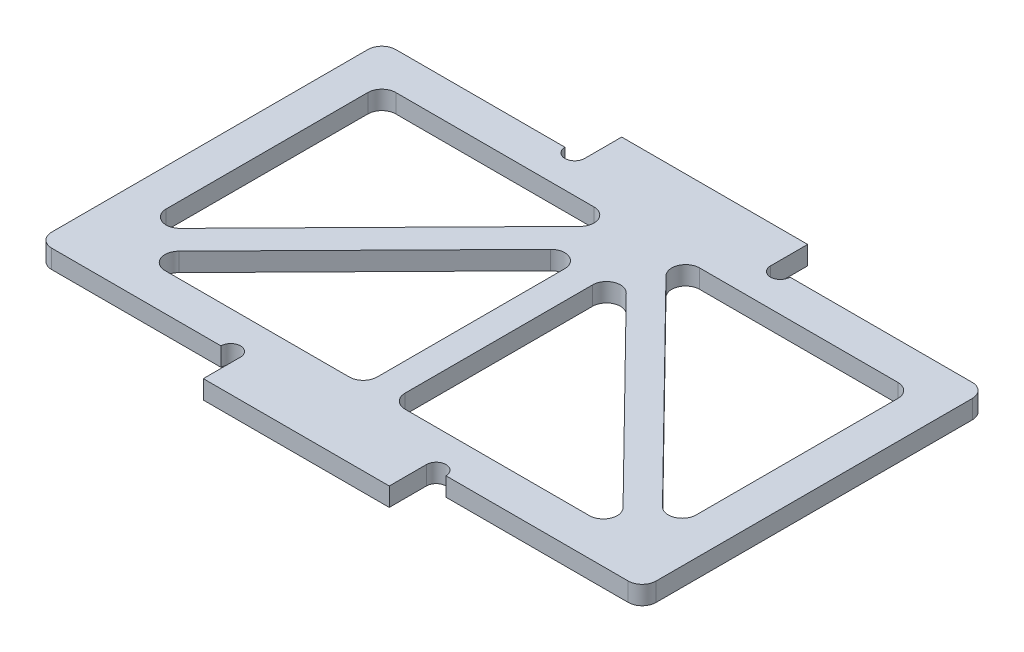
SolidWorks part; units mm, degrees
material "Thornel Mat VMA"
ref_plane "前视基准面" through (0, 0, 0) normal (0, 0, 1) x (1, 0, 0)
ref_plane "上视基准面" through (0, 0, 0) normal (0, 1, 0) x (1, 0, 0)
ref_plane "右视基准面" through (0, 0, 0) normal (1, 0, 0) x (0, 0, -1)
sketch "草图1" plane through (0, 0, 0) normal (0, 1, 0) x (1, 0, 0)
  line L1 (-32.5, -18.5) -> (32.5, -18.5)
  line L2 (-32.5, -18.5) -> (-32.5, 18.5)
  line L3 (-32.5, 18.5) -> (32.5, 18.5)
  line L4 (32.5, -18.5) -> (32.5, 18.5)
  line L5 (-32.5, -18.5) -> (32.5, 18.5) construction
  line L6 (-32.5, 18.5) -> (32.5, -18.5) construction
  point P0 (0, 0)
  dimension "D1" = 37
  dimension "D2" = 65
extrude "凸台-拉伸1" add sketch "草图1" along normal blind 2
sketch "草图2" plane through (0, 0, -18.5) normal (0, 0, -1) x (-1, 0, 0)
  line L0 (10.7, 0) -> (10.7, 2) construction
  line L1 (-9.3, 2) -> (-9.3, 0) construction
  line L2 (10.7, 0) -> (10.7, 2)
  line L3 (-9.3, 2) -> (-9.3, 0)
  line L4 (-9.3, 2) -> (10.7, 2)
  line L5 (-9.3, 0) -> (10.7, 0)
extrude "凸台-拉伸2" add sketch "草图2" along normal blind 4
mirror "镜向1" about plane through (0, 0, 0) normal (0, 0, 1) of "凸台-拉伸2"
sketch "草图3" plane through (0, 2, 0) normal (0, 1, 0) x (1, 0, 0)
  line L0 (9.3, -18.5) -> (32.5, -18.5) construction
  line L1 (-32.5, -18.5) -> (-10.7, -18.5) construction
  line L2 (-10.7, 18.5) -> (-32.5, 18.5) construction
  line L3 (32.5, 18.5) -> (9.3, 18.5) construction
  circle A0 centre (10.35, -18.5) radius 1.05
  circle A1 centre (-11.75, -18.5) radius 1.05
  circle A2 centre (-11.75, 18.5) radius 1.05
  circle A3 centre (10.35, 18.5) radius 1.05
  dimension "D1" = 2.1
extrude "切除-拉伸1" cut sketch "草图3" against normal blind 4
sketch "草图4" plane through (0, 2, 0) normal (0, 1, 0) x (1, 0, 0)
  line L0 (32.5, -18.5) -> (32.5, 18.5) construction
  line L1 (-28.5, -14.5) -> (28.5, -14.5)
  line L2 (-28.5, -14.5) -> (-28.5, 14.5)
  line L3 (-28.5, 14.5) -> (28.5, 14.5)
  line L4 (28.5, -14.5) -> (28.5, 14.5)
  line L5 (0, 14.5) -> (0, -14.5) construction
  line L6 (-28.5, 0) -> (28.5, 0) construction
  line L7 (32.5, 18.5) -> (11.4, 18.5) construction
  line L8 (0, 14.5) -> (-28.5, -14.5) construction
  line L9 (0, 14.5) -> (28.5, -14.5) construction
  line L10 (-1.0698, 13.4486) -> (27.4302, -15.5514)
  line L11 (-1.0698, 15.5514) -> (-29.5698, -13.4486)
  line L12 (-1.5, 14.5) -> (-1.5, -14.5)
  line L13 (1.0698, 15.5514) -> (29.5698, -13.4486)
  line L14 (1.0698, 13.4486) -> (-27.4302, -15.5514)
  line L15 (1.5, 14.5) -> (1.5, -14.5)
  arc A0 (-1.0698, 13.4486) -> (1.0698, 15.5514) centre (0, 14.5) cw
  arc A1 (27.4302, -15.5514) -> (29.5698, -13.4486) centre (28.5, -14.5) ccw
  arc A2 (-1.0698, 15.5514) -> (1.0698, 13.4486) centre (0, 14.5) cw
  arc A3 (-29.5698, -13.4486) -> (-27.4302, -15.5514) centre (-28.5, -14.5) ccw
  arc A4 (-1.5, 14.5) -> (1.5, 14.5) centre (0, 14.5) cw
  arc A5 (-1.5, -14.5) -> (1.5, -14.5) centre (0, -14.5) ccw
  point P0 (0, 0)
  dimension "D1" = 4
  dimension "D2" = 4
  dimension "D3" = 1.5
  dimension "D4" = 1.5
extrude "切除-拉伸2" cut sketch "草图4" against normal blind 10 contours L11 L3 L2 | L12 L14 L1 | L10 L15 L1 | L3 L13 L4
fillet "圆角1" radius 1.5 16 edges at (-32.5, 1, -18.5) (-32.5, 1, 18.5) (32.5, 1, 18.5) (32.5, 1, -18.5) (-26.3969, 1, 14.5) (-1.5, 1, -10.8337) (-1.5, 1, 14.5) (1.5, 1, 14.5) (1.5, 1, -10.8337) (26.3969, 1, 14.5) (28.5, 1, 12.36) (-28.5, 1, -14.5) (-2.1031, 1, -14.5) (-28.5, 1, 12.36) (2.1031, 1, -14.5) (28.5, 1, -14.5)
